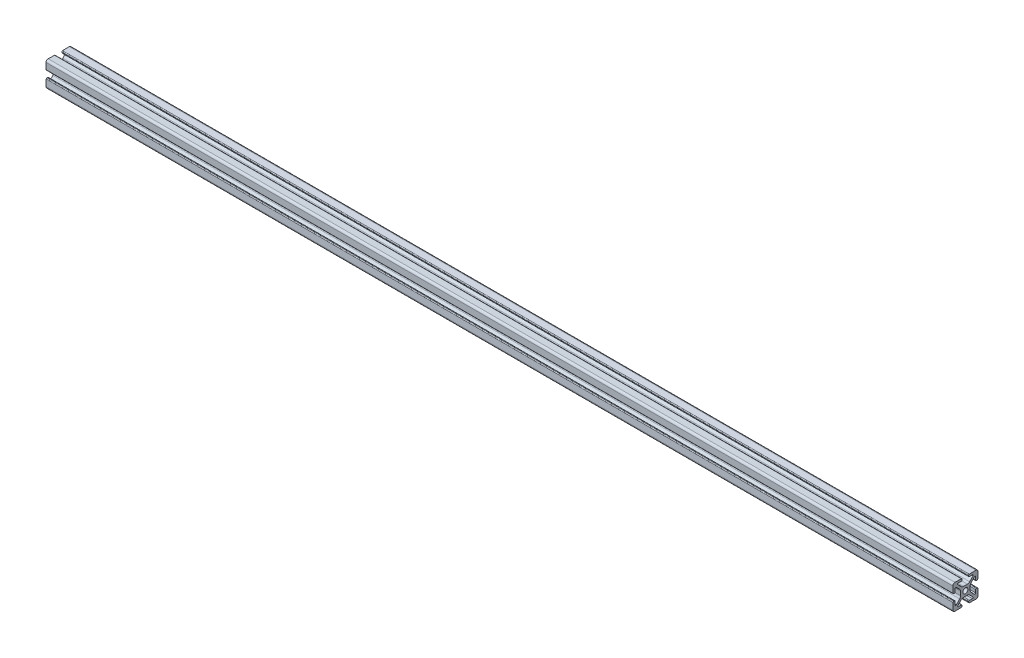
SolidWorks part; units mm, degrees
ref_plane "Front Plane" through (0, 0, 0) normal (0, 0, 1) x (1, 0, 0)
ref_plane "Top Plane" through (0, 0, 0) normal (0, 1, 0) x (1, 0, 0)
ref_plane "Right Plane" through (0, 0, 0) normal (1, 0, 0) x (0, 0, -1)
sketch "Sketch1" plane through (0, 0, 0) normal (1, 0, 0) x (0, 0, -1)
  line L0 (0, -12.7) -> (0, 12.7) construction
  line L1 (-7.874, 12.7) -> (7.874, 12.7) construction
  line L2 (-12.7, 0) -> (12.7, 0) construction
  line L3 (-7.874, 12.7) -> (-7.874, 4.826) construction
  line L4 (-3.302, 12.7) -> (3.302, 12.7) construction
  line L5 (-12.7, -12.7) -> (12.7, -12.7) construction
  line L6 (-12.7, 12.7) -> (12.7, 12.7) construction
  circle A0 centre (0, 0) radius 2.54 construction
  point P7 (0, 12.7)
  point P10 (0, 0)
  point P13 (0, 0)
  point P16 (0, 12.7)
  point P17 (-3.302, 12.7)
  point P18 (3.302, 12.7)
  point P21 (0, -12.7)
  point P24 (0, 12.7)
  dimension "Center Hole Diameter" = 5.08
  dimension "Rail Width" = 25.4
  dimension "Rail Height" = 25.4
  dimension "T-Slot Depth" = 7.874
  dimension "D1" = 15.748
  dimension "T-Slot Width" = 6.604
  dimension "D2" = 12.7
sketch "Sketch2" plane through (0, 0, 0) normal (0, 0, 1) x (1, 0, 0)
  line L0 (-457.2, 0) -> (457.2, 0) construction
  line L1 (0, 0) -> (0, 26.104) construction
  line L2 (457.2, -12.7) -> (457.2, 12.7) construction
  line L3 (-457.2, -12.7) -> (-457.2, 12.7) construction
  point P3 (-419.1, 0)
  point P8 (0, 0)
  point P9 (419.1, 0)
  point P12 (457.2, 0)
  point P15 (-457.2, 0)
  dimension "Length" = 914.4
  dimension "D1" = 38.1
  dimension "D2" = 25.4
sketch "Sketch3" plane through (0, 0, 0) normal (1, 0, 0) x (0, 0, -1)
  line L0 (0, 4.826) -> (1.9842, 4.826)
  line L1 (0, -12.7) -> (0, 12.7) construction
  line L2 (4.2293, 5.7559) -> (7.5866, 9.1132)
  line L6 (7.0212, 10.4136) -> (4.0906, 10.3112)
  line L7 (3.302, 11.0728) -> (3.302, 11.7082)
  line L8 (-7.874, 12.7) -> (7.874, 12.7) construction
  line L10 (0, 0) -> (12.7, 12.7) construction
  line L13 (0, 4.826) -> (0, 2.54)
  line L14 (4.826, 0) -> (2.54, 0)
  line L31 (4.826, 0) -> (4.826, 1.9842)
  line L32 (4.0374, 12.4697) -> (10.5971, 12.6988)
  line L33 (-12.7, 0) -> (12.7, 0) construction
  line L34 (-12.7, 12.7) -> (12.7, 12.7) construction
  line L35 (5.7559, 4.2293) -> (9.1132, 7.5866)
  line L36 (0, 12.7) -> (12.7, 12.7) construction
  line L37 (12.7, 12.7) -> (12.7, 8.0234) construction
  line L38 (11.0728, 3.302) -> (11.7082, 3.302)
  line L39 (10.4136, 7.0212) -> (10.3112, 4.0906)
  line L40 (12.6988, 10.5971) -> (12.4697, 4.0374)
  arc A0 (2.54, 0) -> (0, 2.54) centre (0, 0) ccw
  arc A1 (1.9842, 4.826) -> (4.2293, 5.7559) centre (1.9842, 8.001) ccw
  circle A2 centre (0, 0) radius 2.54 construction
  arc A7 (3.302, 11.7082) -> (4.0374, 12.4697) centre (4.064, 11.7082) cw
  arc A8 (4.0906, 10.3112) -> (3.302, 11.0728) centre (4.064, 11.0728) cw
  arc A14 (4.826, 1.9842) -> (5.7559, 4.2293) centre (8.001, 1.9842) cw
  arc A16 (10.5971, 12.6988) -> (12.6988, 10.5971) centre (10.668, 10.668) cw
  arc A17 (7.0212, 10.4136) -> (7.5866, 9.1132) centre (7.0478, 9.652) cw
  arc A18 (10.4136, 7.0212) -> (9.1132, 7.5866) centre (9.652, 7.0478) ccw
  arc A19 (10.3112, 4.0906) -> (11.0728, 3.302) centre (11.0728, 4.064) ccw
  arc A20 (11.7082, 3.302) -> (12.4697, 4.0374) centre (11.7082, 4.064) ccw
  point P37 (3.2994, 4.826)
  point P49 (12.7, 3.302)
  point P52 (3.302, 12.7)
  point P55 (3.302, 10.2837)
  dimension "D4" = 3.175
  dimension "D9" = 2.159
  dimension "D12" = 0.762
  dimension "D3" = 2.032
  dimension "D8" = 0.762
  dimension "D2" = 45
  dimension "D5" = 2
  dimension "D6" = 45
  dimension "D7" = 2.159
extrude "Boss-Extrude1" add sketch "Sketch3" against normal up to vertex (457.2 mm away) and the other way up to vertex (457.2 mm away) up to point (-457.2, 0, 0) other way up to point (457.2, 0, 0)
mirror "Mirror1" about plane through (0, 0, 0) normal (0, 1, 0) of bodies 104
mirror "Mirror2" about plane through (0, 0, 0) normal (0, 0, 1) of bodies 105
equation "\"D1@Sketch2\"=\"Rail Height@Sketch1\"*1.5"
equation "\"D2@Sketch2\"=\"Rail Height@Sketch1\""
